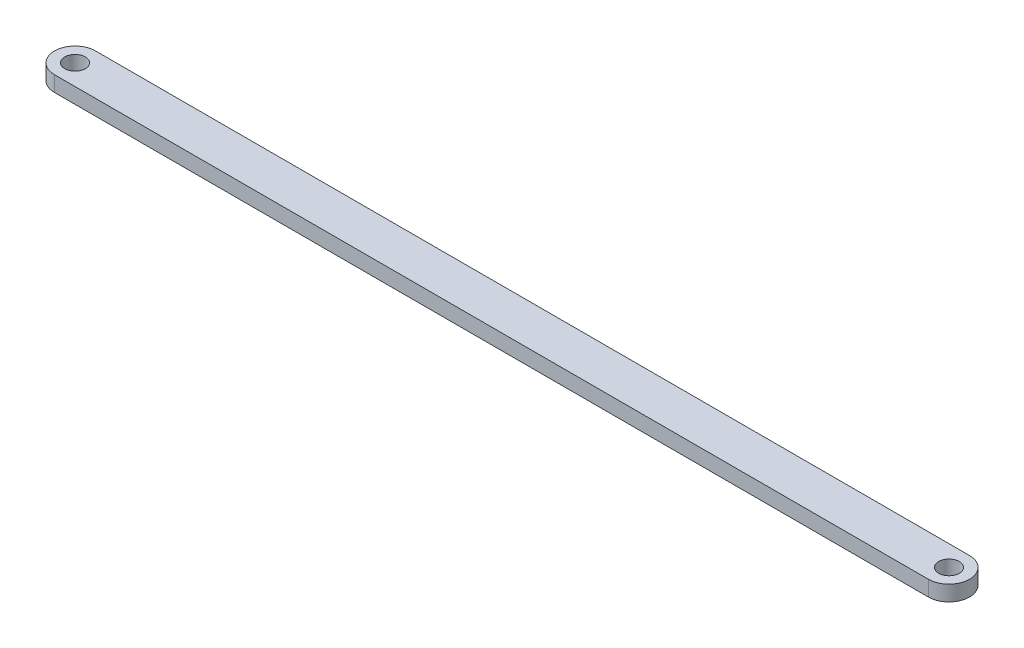
SolidWorks part; units mm, degrees
ref_plane "Front Plane" through (0, 0, 0) normal (0, 0, 1) x (1, 0, 0)
ref_plane "Top Plane" through (0, 0, 0) normal (0, 1, 0) x (1, 0, 0)
ref_plane "Right Plane" through (0, 0, 0) normal (1, 0, 0) x (0, 0, -1)
sketch "Sketch1" plane through (0, 0, 0) normal (0, 1, 0) x (1, 0, 0)
  line L0 (170, 0) -> (0, 0) construction
  line L1 (0, 4) -> (170, 4)
  line L2 (0, -4) -> (170, -4)
  circle A0 centre (0, 0) radius 2
  circle A1 centre (170, 0) radius 2
  circle A2 centre (0, 0) radius 4
  circle A3 centre (170, 0) radius 4
  point P21 (0, 0)
  point P22 (0, 0)
  point P23 (0, 0)
  dimension "D1" = 4
  dimension "D2" = 4
  dimension "D4" = 2
  dimension "D5" = 2
  dimension "D3" = 170
extrude "Boss-Extrude1" add sketch "Sketch1" along normal blind 3
